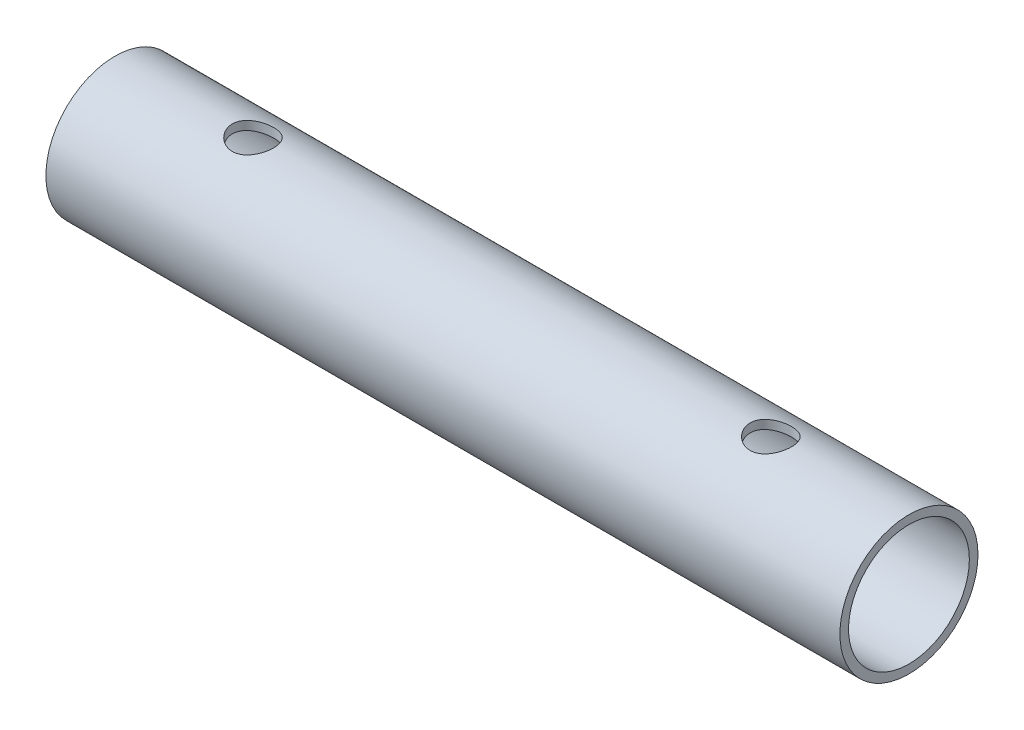
SolidWorks part; units mm, degrees
ref_plane "Front" through (0, 0, 0) normal (0, 0, 1) x (1, 0, 0)
ref_plane "Top" through (0, 0, 0) normal (0, 1, 0) x (1, 0, 0)
ref_plane "Right" through (0, 0, 0) normal (1, 0, 0) x (0, 0, -1)
sketch "草图1" plane through (0, 0, 0) normal (1, 0, 0) x (0, 0, -1)
  circle A0 centre (0, 0) radius 8.75
  circle A1 centre (0, 0) radius 10
extrude "凸台-拉伸1" add sketch "草图1" along normal blind 115
sketch "草图2" plane through (0, 0, 0) normal (0, 1, 0) x (1, 0, 0)
  line L0 (0, 0) -> (20, 0) construction
  line L1 (0, 0) -> (95, 0) construction
  circle A0 centre (20, 0) radius 3
  circle A1 centre (95, 0) radius 3
extrude "切除-拉伸1" cut sketch "草图2" against normal through all both and the other way through all
